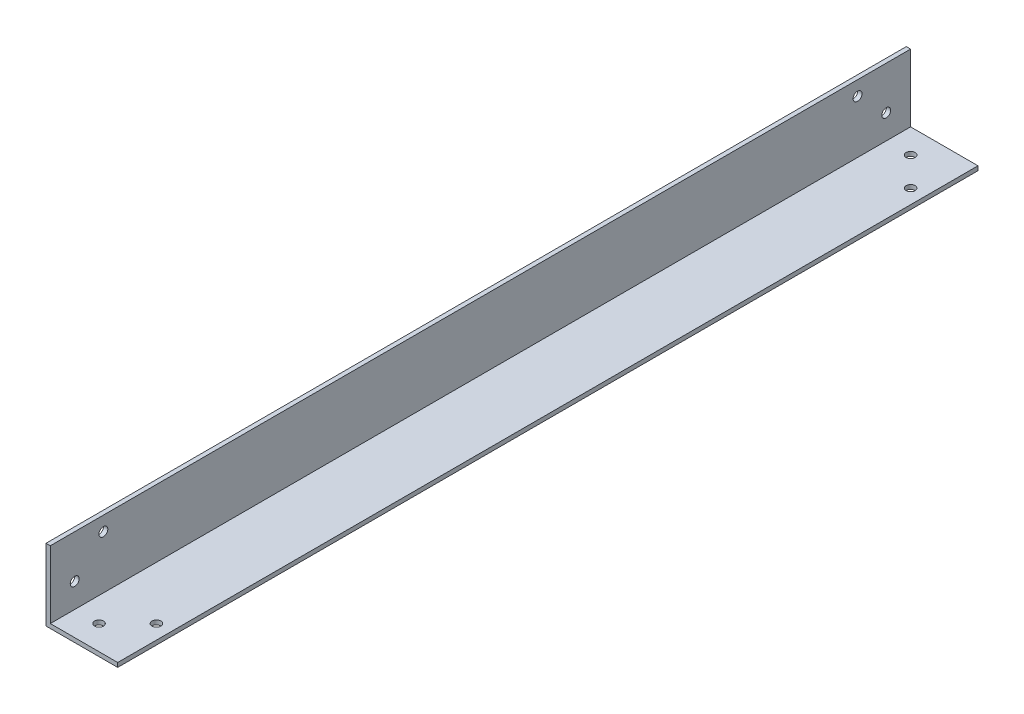
SolidWorks part; units mm, degrees
ref_plane "Front Plane" through (0, 0, 0) normal (0, 0, 1) x (1, 0, 0)
ref_plane "Top Plane" through (0, 0, 0) normal (0, 1, 0) x (1, 0, 0)
ref_plane "Right Plane" through (0, 0, 0) normal (1, 0, 0) x (0, 0, -1)
sketch "Sketch1" plane through (0, 0, 0) normal (0, 0, 1) x (1, 0, 0)
  line L0 (0, 0) -> (0, 25)
  line L1 (0, 25) -> (1.5, 25)
  line L2 (1.5, 25) -> (1.5, 1.5)
  line L3 (1.5, 1.5) -> (25, 1.5)
  line L4 (25, 1.5) -> (25, 0)
  line L5 (25, 0) -> (0, 0)
  dimension "D1" = 1.5
  dimension "D2" = 25
extrude "Boss-Extrude1" add sketch "Sketch1" along normal blind 300
sketch "Sketch2" plane through (0, 0, 0) normal (-1, 0, 0) x (0, 0, 1)
  line L0 (291.5, 10) -> (8.5, 10) construction
  line L1 (18.5, 20) -> (281.5, 20) construction
  line L2 (300, 25) -> (0, 25) construction
  line L3 (0, 25) -> (0, 0) construction
  line L4 (300, 25) -> (300, 0) construction
  circle A0 centre (281.5, 20) radius 1.55
  circle A1 centre (291.5, 10) radius 1.55
  circle A2 centre (18.5, 20) radius 1.55
  circle A3 centre (8.5, 10) radius 1.55
  dimension "D1" = 3.1
  dimension "D2" = 5
  dimension "D3" = 15
  dimension "D4" = 8.5
  dimension "D5" = 18.5
  dimension "D6" = 18.5
  dimension "D7" = 8.5
extrude "Cut-Extrude1" cut sketch "Sketch2" against normal blind 10
sketch "Sketch3" plane through (0, 0, 0) normal (0, -1, 0) x (1, 0, 0)
  line L0 (20, 18.5) -> (20, 281.5) construction
  line L1 (10, 291.5) -> (10, 8.5) construction
  line L2 (25, 300) -> (25, 0) construction
  line L4 (0, 0) -> (25, 0) construction
  line L5 (0, 300) -> (25, 300) construction
  circle A0 centre (20, 281.5) radius 1.55
  circle A1 centre (10, 291.5) radius 1.55
  circle A2 centre (20, 18.5) radius 1.55
  circle A3 centre (10, 8.5) radius 1.55
  dimension "D7" = 3.1
  dimension "D1" = 5
  dimension "D2" = 15
  dimension "D3" = 8.5
  dimension "D4" = 18.5
  dimension "D5" = 8.5
  dimension "D6" = 18.5
extrude "Cut-Extrude2" cut sketch "Sketch3" against normal blind 10
